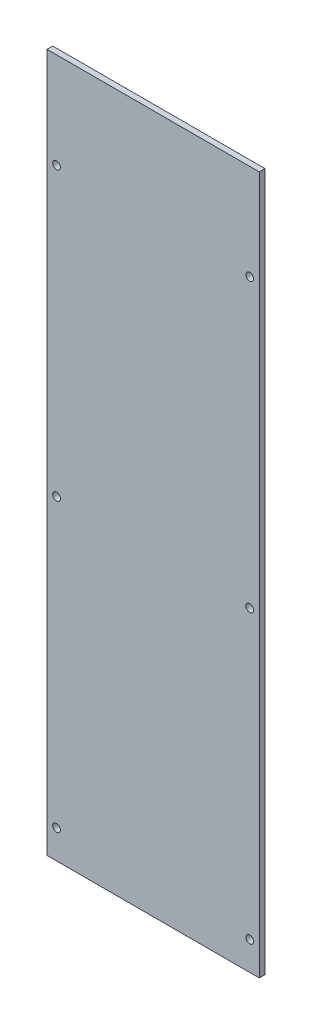
SolidWorks part; units mm, degrees
material "Acrylic (Medium-high impact)"
ref_plane "Front Plane" through (0, 0, 0) normal (0, 0, 1) x (1, 0, 0)
ref_plane "Top Plane" through (0, 0, 0) normal (0, 1, 0) x (1, 0, 0)
ref_plane "Right Plane" through (0, 0, 0) normal (1, 0, 0) x (0, 0, -1)
sketch "Sketch1" plane through (0, 0, 0) normal (0, 0, 1) x (1, 0, 0)
  line L0 (-50.5, 135) -> (-50.5, 185) construction
  line L1 (50.5, 135) -> (50.5, 185) construction
  line L2 (-55.5, 185) -> (55.5, 185)
  line L4 (-55.5, 185) -> (-55.5, -180)
  line L5 (55.5, -180) -> (-55.5, -180)
  line L6 (55.5, -180) -> (55.5, 185)
  circle A0 centre (50.5, -15) radius 2
  circle A1 centre (-50.5, -15) radius 2
  circle A2 centre (-50.5, -165) radius 2
  circle A3 centre (50.5, -165) radius 2
  circle A4 centre (50.5, 135) radius 2
  circle A5 centre (-50.5, 135) radius 2
  dimension "D8" = 4
  dimension "D1" = 5
  dimension "D2" = 5
  dimension "D3" = 111
  dimension "D4" = 365
  dimension "D5" = 50
  dimension "D6" = 150
  dimension "D7" = 150
  dimension "D9" = 50.5
  dimension "D10" = 135
extrude "Boss-Extrude1" add sketch "Sketch1" along normal blind 3
